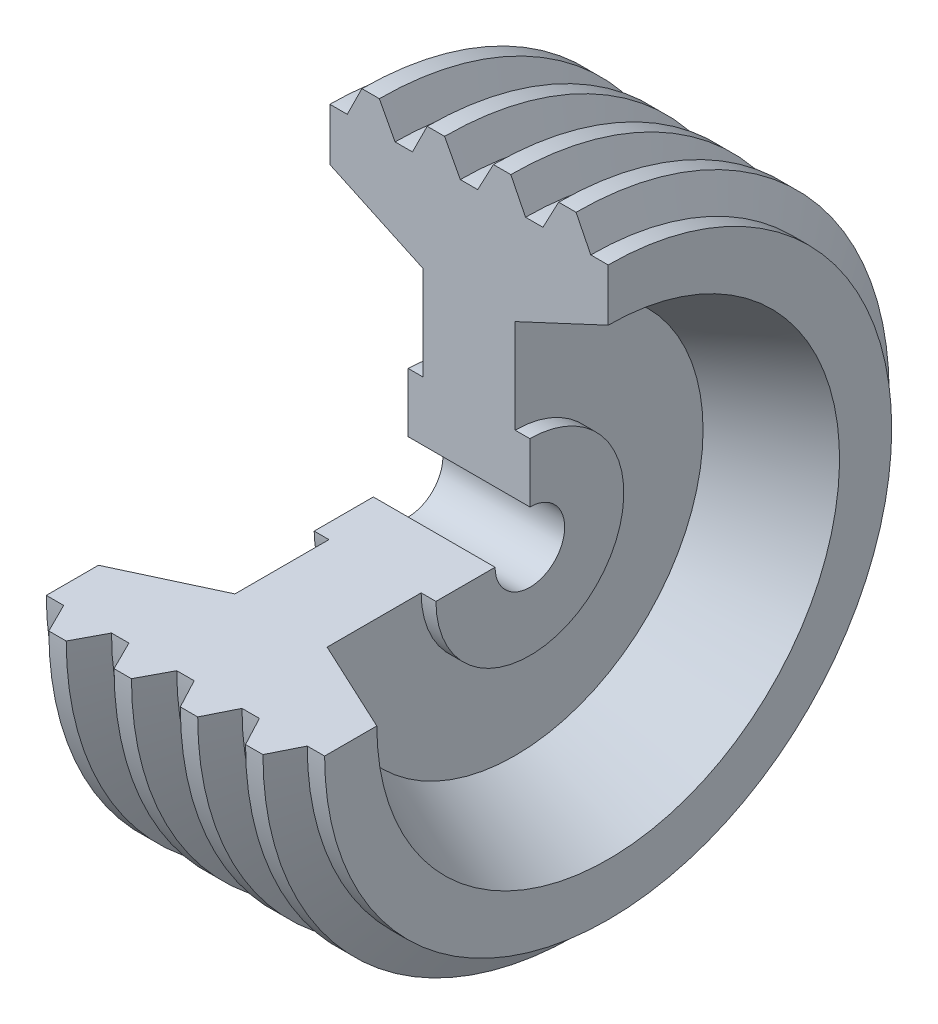
SolidWorks part; units mm, degrees
ref_plane "Front Plane" through (0, 0, 0) normal (0, 0, 1) x (1, 0, 0)
ref_plane "Top Plane" through (0, 0, 0) normal (0, 1, 0) x (1, 0, 0)
ref_plane "Right Plane" through (0, 0, 0) normal (1, 0, 0) x (0, 0, -1)
sketch "Sketch1" plane through (0, 0, 0) normal (0, 0, 1) x (1, 0, 0)
  line L0 (0, 0) -> (44496.8417, 0) construction
  line L1 (0, 0) -> (0, 44496.8417) construction
  line L2 (-35, 20) -> (35, 20)
  line L3 (35, 20) -> (35, 54)
  line L4 (35, 54) -> (26.5, 54)
  line L5 (26.5, 54) -> (26.5, 108.0525)
  line L6 (26.5, 108.0525) -> (80, 133)
  line L7 (80, 133) -> (80, 163)
  line L8 (80, 163) -> (70, 163)
  line L9 (70, 163) -> (61.5391, 180)
  line L10 (61.5391, 180) -> (51.5391, 180)
  line L11 (51.5391, 180) -> (42.5, 163)
  line L12 (42.5, 163) -> (32.5, 163)
  line L13 (32.5, 163) -> (24.0391, 180)
  line L14 (24.0391, 180) -> (14.0391, 180)
  line L15 (14.0391, 180) -> (5, 163)
  line L16 (5, 163) -> (-5, 163)
  line L17 (-14.0391, 180) -> (-5, 163)
  line L18 (-24.0391, 180) -> (-14.0391, 180)
  line L19 (-32.5, 163) -> (-24.0391, 180)
  line L20 (-42.5, 163) -> (-32.5, 163)
  line L21 (-51.5391, 180) -> (-42.5, 163)
  line L22 (-61.5391, 180) -> (-51.5391, 180)
  line L23 (-70, 163) -> (-61.5391, 180)
  line L24 (-80, 163) -> (-70, 163)
  line L25 (-80, 133) -> (-80, 163)
  line L26 (-26.5, 108.0525) -> (-80, 133)
  line L27 (-26.5, 54) -> (-26.5, 108.0525)
  line L28 (-35, 54) -> (-26.5, 54)
  line L29 (-35, 20) -> (-35, 54)
  point P5 (35, 37)
  point P20 (60.2149, 180)
  point P22 (0, 0)
  point P24 (0, 163)
  point P37 (0, 20)
  dimension "D1" = 17
  dimension "D2" = 30
  dimension "D3" = 40
  dimension "D4" = 360
  dimension "D5" = 108
  dimension "D6" = 10
  dimension "D7" = 62
  dimension "D8" = 160
  dimension "D9" = 65
  dimension "D10" = 53
  dimension "D11" = 70
revolve "Revolve1" add sketch "Sketch1" angle 270 about L0
